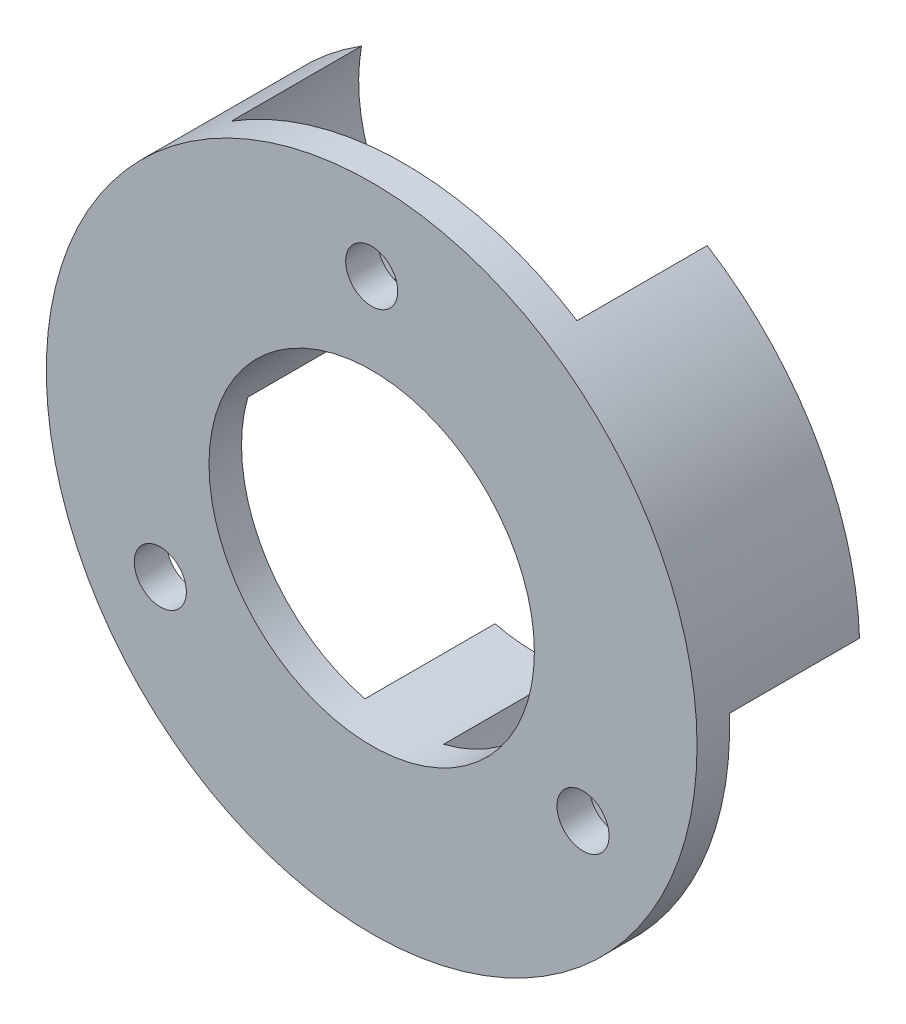
SolidWorks part; units mm, degrees
ref_plane "Front Plane" through (0, 0, 0) normal (0, 0, 1) x (1, 0, 0)
ref_plane "Top Plane" through (0, 0, 0) normal (0, 1, 0) x (1, 0, 0)
ref_plane "Right Plane" through (0, 0, 0) normal (1, 0, 0) x (0, 0, -1)
sketch "Sketch1" plane through (0, 0, 0) normal (0, 0, 1) x (1, 0, 0)
  circle A0 centre (0, 0) radius 25
  dimension "D1" = 50
extrude "Boss-Extrude1" add sketch "Sketch1" along normal blind 2.5 contours A0
sketch "Sketch3" plane through (0, 0, 0) normal (0, 0, -1) x (-1, 0, 0)
  line L0 (0, 7.5) -> (0, 18.75) construction
  arc A4 (-11.7043, -22.091) -> (-3.0219, -12.1292) centre (-16.238, -9.375) ccw
  arc A5 (-13.2792, 21.1817) -> (-8.9933, 8.6817) centre (0, 18.75) ccw
  arc A6 (24.9835, 0.9093) -> (11.7043, -22.091) centre (16.238, -9.375) ccw
  circle A7 centre (0, 0) radius 12.5
  arc A8 (-11.7043, -22.091) -> (13.2792, 21.1817) centre (0, 0) ccw
  arc A9 (8.9933, 8.6817) -> (13.2792, 21.1817) centre (0, 18.75) ccw
  arc A10 (-12.0152, 3.4476) -> (-24.9835, 0.9093) centre (-16.238, -9.375) ccw
  arc A11 (-13.2792, 21.1817) -> (-24.9835, 0.9093) centre (0, 0) ccw
  point P13 (0, 0)
  point P19 (0, 0)
  dimension "D2" = 11.25
  dimension "D5" = 27
  dimension "D7" = 25
  dimension "D6" = 3
extrude "Boss-Extrude2" add sketch "Sketch3" along normal blind 10 contours A10 A7 A5 L0 | A7 A4 L0 A6 | A9 A7 A6 L0
sketch "Sketch4" plane through (0, 0, 0) normal (0, 0, -1) x (-1, 0, 0)
  circle A0 centre (0, 0) radius 12.5
extrude "Cut-Extrude1" cut sketch "Sketch4" against normal blind 8.2
sketch "Sketch6" plane through (0, 0, -10) normal (0, 0, -1) x (-1, 0, 0)
  line L0 (10.8253, 6.25) -> (21.6506, 12.5) construction
  arc A0 (12.0152, 3.4476) -> (8.9933, 8.6817) centre (0, 0) ccw construction
  arc A1 (24.9835, 0.9093) -> (13.2792, 21.1817) centre (0, 0) ccw construction
  circle A2 centre (16.238, 9.375) radius 2
  circle A3 centre (0, -18.75) radius 2
  circle A4 centre (-16.238, 9.375) radius 2
  point P16 (0, 0)
  dimension "D1" = 4
  dimension "D2" = 3
extrude "Cut-Extrude3" cut sketch "Sketch6" against normal blind 6
sketch "Sketch8" plane through (0, 0, 0) normal (0, 0, -1) x (-1, 0, 0)
  line L0 (-10.8253, -6.25) -> (-21.6506, -12.5) construction
  arc A0 (-12.0152, 3.4476) -> (-3.0219, -12.1292) centre (0, 0) ccw construction
  arc A1 (-24.9835, 0.9093) -> (-11.7043, -22.091) centre (0, 0) ccw construction
  circle A2 centre (-16.238, -9.375) radius 2
  circle A3 centre (0, 18.75) radius 2
  circle A4 centre (16.238, -9.375) radius 2
  point P16 (0, 0)
  dimension "D1" = 4
  dimension "D2" = 3
extrude "Cut-Extrude4" cut sketch "Sketch8" against normal blind 6
